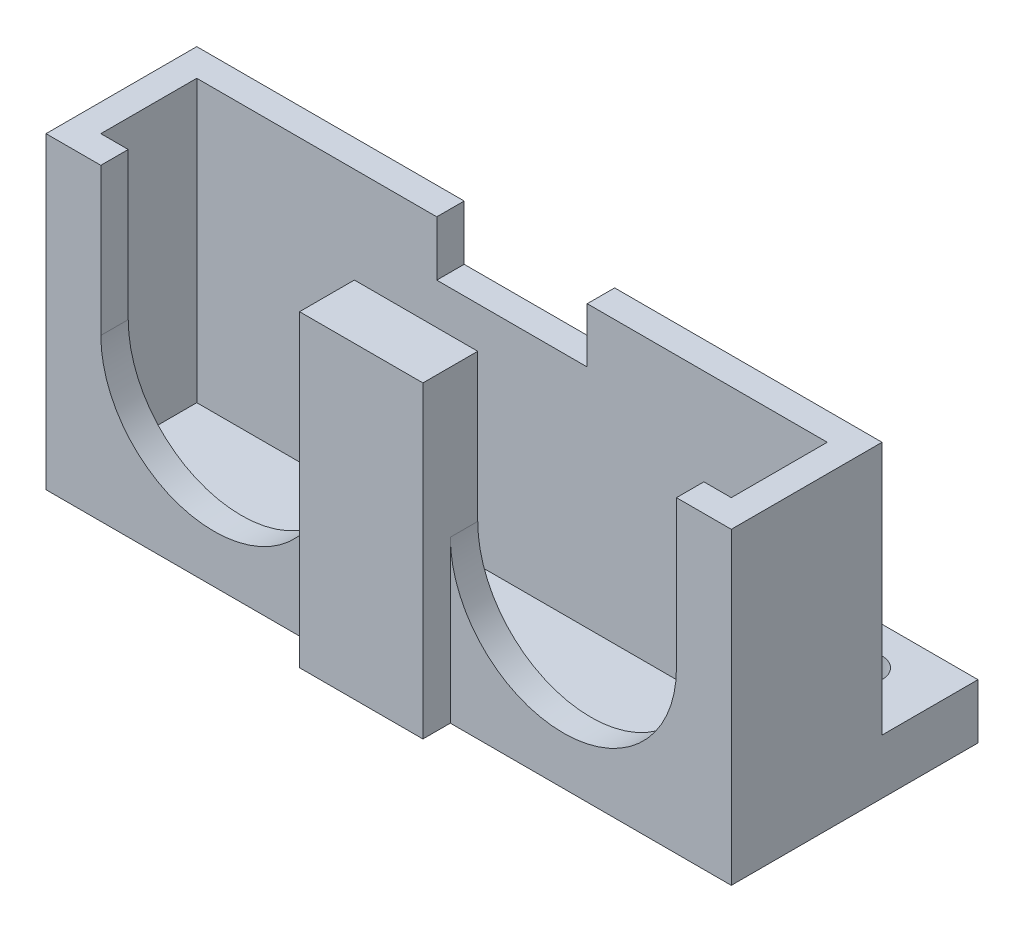
SolidWorks part; units mm, degrees
ref_plane "Plano frontal" through (0, 0, 0) normal (0, 0, 1) x (1, 0, 0)
ref_plane "Plano superior" through (0, 0, 0) normal (0, 1, 0) x (1, 0, 0)
ref_plane "Plano direito" through (0, 0, 0) normal (1, 0, 0) x (0, 0, -1)
sketch "Esboço1" plane through (0, 0, 0) normal (0, 1, 0) x (1, 0, 0)
  line L1 (-25, 5.5) -> (25, 5.5)
  line L2 (-25, 5.5) -> (-25, -5.5)
  line L3 (-25, -5.5) -> (25, -5.5)
  line L4 (25, 5.5) -> (25, -5.5)
  line L5 (-25, 5.5) -> (25, -5.5) construction
  line L6 (-25, -5.5) -> (25, 5.5) construction
  point P0 (0, 0)
  dimension "D1" = 50
  dimension "D2" = 11
extrude "Ressalto-extrusão1" add sketch "Esboço1" along normal blind 22.5
sketch "Esboço2" plane through (0, 22.5, 0) normal (0, 1, 0) x (1, 0, 0)
  line L1 (-23, 3.5) -> (23, 3.5)
  line L2 (-23, 3.5) -> (-23, -3.5)
  line L3 (-23, -3.5) -> (23, -3.5)
  line L4 (23, 3.5) -> (23, -3.5)
  line L5 (-23, 3.5) -> (23, -3.5) construction
  line L6 (-23, -3.5) -> (23, 3.5) construction
  point P0 (0, 0)
extrude "Corte-extrusão1" cut sketch "Esboço2" against normal blind 20.5
sketch "Esboço3" plane through (0, 22.5, 0) normal (0, 1, 0) x (1, 0, 0)
  line L3 (23, 3.5) -> (-23, 3.5) construction
  line L4 (-5.4896, 5.5) -> (5.4896, 5.5)
  line L5 (-5.4896, 5.5) -> (-5.4896, 3.5)
  line L6 (-5.4896, 3.5) -> (5.4896, 3.5)
  line L7 (5.4896, 5.5) -> (5.4896, 3.5)
  line L8 (-5.4896, 5.5) -> (5.4896, 3.5) construction
  line L9 (-5.4896, 3.5) -> (5.4896, 5.5) construction
  point P6 (0, 4.5)
extrude "Corte-extrusão2" cut sketch "Esboço3" against normal blind 4
sketch "Esboço5" plane through (0, 0, 5.5) normal (0, 0, 1) x (1, 0, 0)
  line L0 (-25, 22.5) -> (25, 22.5) construction
  line L1 (-21, 22.5) -> (-4.5, 22.5)
  line L2 (-21, 22.5) -> (-21, 11.75)
  line L4 (-4.5, 22.5) -> (-4.5, 11.75)
  line L5 (-25, 22.5) -> (-25, 0) construction
  line L7 (4.5, 22.5) -> (21, 22.5)
  line L8 (4.5, 22.5) -> (4.5, 11.75)
  line L10 (21, 22.5) -> (21, 11.75)
  line L11 (25, 22.5) -> (25, 0) construction
  arc A0 (-21, 11.75) -> (-4.5, 11.75) centre (-12.75, 11.75) ccw
  arc A1 (4.5, 11.75) -> (21, 11.75) centre (12.75, 11.75) ccw
  dimension "D1" = 16.5
  dimension "D2" = 4
  dimension "D3" = 16.5
  dimension "D4" = 4
  dimension "D6" = 0
extrude "Corte-extrusão3" cut sketch "Esboço5" against normal blind 4
sketch "Esboço9" plane through (0, 0, -5.5) normal (0, 0, -1) x (-1, 0, 0)
  line L0 (25, 22.5) -> (25, 0) construction
  line L1 (-25, 0) -> (25, 0)
  line L2 (-25, 0) -> (-25, 4)
  line L3 (-25, 4) -> (25, 4)
  line L4 (25, 0) -> (25, 4)
  dimension "D1" = 4
extrude "Ressalto-extrusão4" add sketch "Esboço9" along normal blind 7
sketch "Esboço13" plane through (0, 4, 0) normal (0, 1, 0) x (1, 0, 0)
  line L0 (25, 12.5) -> (25, 5.5) construction
  circle A0 centre (10, 9) radius 1.5
  circle A1 centre (5, 9) radius 1.5
  circle A2 centre (20, 9) radius 1.5
  circle A3 centre (15, 9) radius 1.5
  circle A4 centre (0, 9) radius 1.5
  circle A5 centre (-5, 9) radius 1.5
  circle A6 centre (-10, 9) radius 1.5
  circle A7 centre (-15, 9) radius 1.5
  circle A8 centre (-20, 9) radius 1.5
extrude "Corte-extrusão4" cut sketch "Esboço13" against normal blind 7
sketch "Esboço19" plane through (0, 22.5, 0) normal (0, 1, 0) x (1, 0, 0)
  line L0 (4.5, -3.5) -> (4.5, -5.5) construction
  line L1 (-4.5, -3.5) -> (4.5, -3.5)
  line L2 (-4.5, -3.5) -> (-4.5, -7.5)
  line L3 (-4.5, -7.5) -> (4.5, -7.5)
  line L4 (4.5, -3.5) -> (4.5, -7.5)
  point P4 (4.5, -4.5)
  dimension "D1" = 4
  dimension "D2" = 0
extrude "Ressalto-extrusão5" add sketch "Esboço19" against normal blind 22.5
